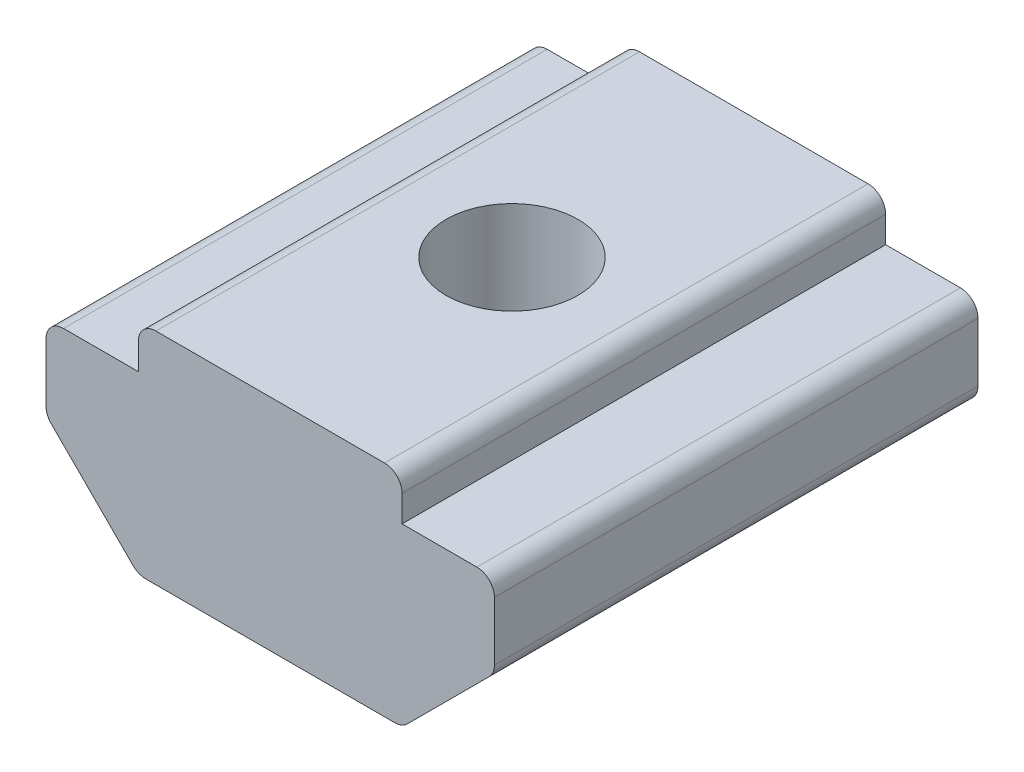
SolidWorks part; units mm, degrees
ref_plane "前视基准面" through (0, 0, 0) normal (0, 0, 1) x (1, 0, 0)
ref_plane "上视基准面" through (0, 0, 0) normal (0, 1, 0) x (1, 0, 0)
ref_plane "右视基准面" through (0, 0, 0) normal (1, 0, 0) x (0, 0, -1)
sketch "草图1" plane through (0, 0, 0) normal (0, 0, 1) x (1, 0, 0)
  line L0 (-5.1, 0) -> (-3, 0)
  line L1 (-3, 0) -> (-3, 1)
  line L2 (-3, 1) -> (3, 1)
  line L3 (3, 1) -> (3, 0)
  line L4 (3, 0) -> (5.1, 0)
  line L5 (5.1, 0) -> (5.1, -1.9)
  line L6 (5.1, -1.9) -> (3, -4)
  line L7 (3, -4) -> (-3, -4)
  line L8 (-3, -4) -> (-5.1, -1.9)
  line L9 (-5.1, -1.9) -> (-5.1, 0)
  point P12 (0, 1)
  dimension "D1" = 5
  dimension "D2" = 4
  dimension "D3" = 10.2
  dimension "D4" = 6
  dimension "D5" = 6
extrude "凸台-拉伸1" add sketch "草图1" along normal mid plane 11
sketch "草图2" plane through (0, 1, 0) normal (0, 1, 0) x (1, 0, 0)
  circle A0 centre (0, 0) radius 1.5
  dimension "D1" = 3
extrude "切除-拉伸1" cut sketch "草图2" against normal through all
fillet "圆角1" radius 0.4 8 edges at (3, 1, 0) (-3, 1, 0) (-5.1, 0, 0) (-5.1, -1.9, 0) (-3, -4, 0) (3, -4, 0) (5.1, -1.9, 0) (5.1, 0, 0)
